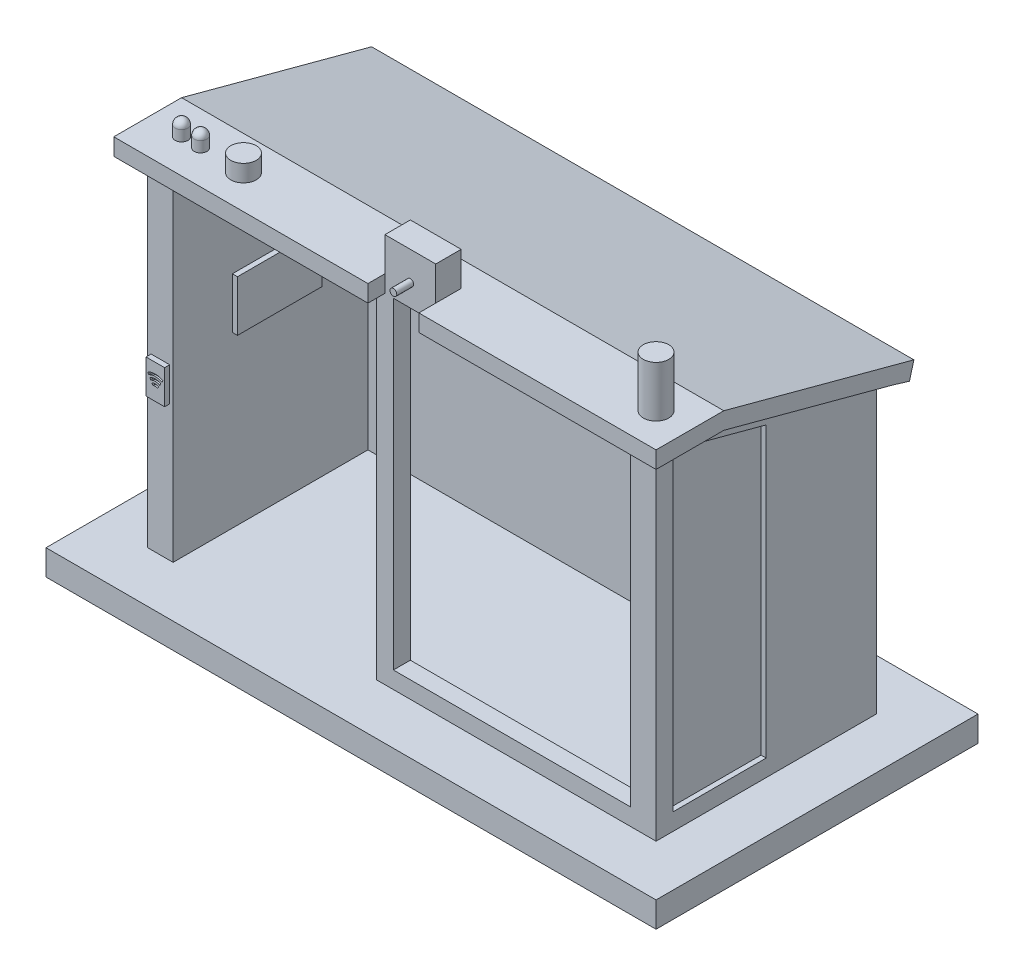
SolidWorks part; units mm, degrees
ref_plane "Alzado" through (0, 0, 0) normal (0, 0, 1) x (1, 0, 0)
ref_plane "Planta" through (0, 0, 0) normal (0, 1, 0) x (1, 0, 0)
ref_plane "Vista lateral" through (0, 0, 0) normal (1, 0, 0) x (0, 0, -1)
sketch "Croquis4" plane through (0, 0, 0) normal (0, 1, 0) x (1, 0, 0)
  line L0 (-150, 65) -> (150, -65) construction
  line L13 (-150, 65) -> (150, 65)
  line L14 (-150, 65) -> (-150, -65)
  line L15 (-150, -65) -> (-135, -65)
  line L16 (150, 65) -> (150, -65)
  line L17 (135, -65) -> (150, -65)
  line L19 (-135, -65) -> (-135, 50)
  line L20 (-135, 50) -> (135, 50)
  line L21 (135, -65) -> (135, 50)
  point P4 (0, 0)
  dimension "D1" = 15
  dimension "D2" = 130
  dimension "D3" = 300
  dimension "D4" = 15
  dimension "D5" = 15
extrude "Saliente-Extruir11" add sketch "Croquis4" along normal blind 200
sketch "Croquis28" plane through (-150, 0, 0) normal (-1, 0, 0) x (0, 0, 1)
  line L0 (-65, 173.2051) -> (35, 200)
  line L1 (-65, 200) -> (-65, 0) construction
  line L2 (-65, 200) -> (65, 200) construction
  line L3 (35, 200) -> (-65, 200)
  line L4 (-65, 200) -> (-65, 173.2051)
  line L5 (65, 200) -> (65, 0) construction
  dimension "D1" = 30
  dimension "D2" = 15
extrude "Cortar-Extruir10" cut sketch "Croquis28" against normal blind 300
sketch "Croquis29" plane through (-150, 0, 0) normal (-1, 0, 0) x (0, 0, 1)
  line L0 (-65, 173.2051) -> (35, 200)
  line L1 (35, 200) -> (65, 200)
  line L2 (65, 200) -> (75, 200)
  line L3 (75, 200) -> (75, 210)
  line L4 (75, 210) -> (35, 210)
  line L5 (35, 210) -> (-67.5, 182.5352)
  line L6 (-67.5, 182.5352) -> (-77.1593, 179.947)
  line L7 (-77.1593, 179.947) -> (-74.5711, 170.2878)
  line L8 (-74.5711, 170.2878) -> (-65, 173.2051)
extrude "Saliente-Extruir12" add sketch "Croquis29" against normal blind 310 and the other way blind 10
sketch "Croquis30" plane through (0, 0, 0) normal (0, -1, 0) x (1, 0, 0)
  line L0 (-180, 95) -> (180, -95) construction
  line L1 (-180, 95) -> (180, 95)
  line L2 (-180, 95) -> (-180, -95)
  line L3 (-180, -95) -> (180, -95)
  line L4 (180, 95) -> (180, -95)
  line L5 (-160, 75) -> (160, 75) construction
  line L6 (160, -65) -> (160, 35) construction
  point P4 (0, 0)
  dimension "D1" = 20
  dimension "D2" = 20
extrude "Saliente-Extruir13" add sketch "Croquis30" along normal blind 15
sketch "Croquis31" plane through (150, 0, 0) normal (1, 0, 0) x (0, 0, -1)
  line L0 (-55, 190) -> (-55, 10)
  line L1 (-55, 10) -> (0, 10)
  line L2 (0, 10) -> (0, 180.269)
  line L3 (0, 180.269) -> (-36.3165, 190)
  line L4 (-36.3165, 190) -> (-55, 190)
  line L5 (65, 173.2051) -> (-35, 200) construction
  line L6 (-65, 200) -> (-35, 200) construction
  line L7 (65, 173.2051) -> (-35, 200) construction
  line L8 (95, 0) -> (-95, 0) construction
  line L9 (-65, 200) -> (-65, 0) construction
  dimension "D1" = 10
  dimension "D2" = 10
  dimension "D3" = 10
  dimension "D4" = 10
extrude "Cortar-Extruir11" cut sketch "Croquis31" against normal blind 15
sketch "Croquis32" plane through (0, 10, 0) normal (0, 1, 0) x (1, 0, 0)
  line L0 (135, 0) -> (150, 0) construction
  line L1 (142, 0) -> (147, 0)
  line L2 (142, 0) -> (142, -55)
  line L3 (142, -55) -> (147, -55)
  line L4 (147, 0) -> (147, -55)
  line L5 (135, -55) -> (150, -55) construction
  line L6 (150, -55) -> (150, 0) construction
  line L7 (135, -55) -> (135, 0) construction
  dimension "D1" = 3
  dimension "D2" = 7
extrude "Saliente-Extruir14" add sketch "Croquis32" along normal blind 180
sketch "Croquis35" plane through (0, 0, 65) normal (0, 0, 1) x (1, 0, 0)
  line L2 (-150, 0) -> (-135, 0) construction
  line L3 (-148, 100) -> (-137, 100)
  line L4 (-148, 100) -> (-148, 80)
  line L5 (-148, 80) -> (-137, 80)
  line L6 (-137, 100) -> (-137, 80)
  line L7 (-150, 200) -> (-150, 0) construction
  line L8 (-135, 177.2243) -> (-135, 0) construction
  dimension "D1" = 100
  dimension "D2" = 80
  dimension "D3" = 2
  dimension "D4" = 2
extrude "Saliente-Extruir15" add sketch "Croquis35" along normal blind 3
sketch "Croquis36" plane through (0, 0, 68) normal (0, 0, 1) x (1, 0, 0)
  line L1 (-143.875, 87.3816) -> (-144.5, 88.4641)
  line L2 (-141.125, 87.3816) -> (-140.5, 88.4641)
  line L4 (-139.875, 89.5466) -> (-139.25, 90.6292)
  line L6 (-145.125, 89.5466) -> (-145.75, 90.6292)
  line L7 (-146.375, 91.7117) -> (-147, 92.7942)
  line L9 (-138.625, 91.7117) -> (-138, 92.7942)
  arc A0 (-140.5, 88.4641) -> (-144.5, 88.4641) centre (-142.5, 85) ccw
  arc A1 (-141.125, 87.3816) -> (-143.875, 87.3816) centre (-142.5, 85) ccw
  arc A2 (-139.875, 89.5466) -> (-145.125, 89.5466) centre (-142.5, 85) ccw
  arc A3 (-139.25, 90.6292) -> (-145.75, 90.6292) centre (-142.5, 85) ccw
  arc A4 (-138.625, 91.7117) -> (-146.375, 91.7117) centre (-142.5, 85) ccw
  arc A5 (-138, 92.7942) -> (-147, 92.7942) centre (-142.5, 85) ccw
  dimension "D1" = 5.5
  dimension "D2" = 8
  dimension "D3" = 10.5
  dimension "D4" = 13
  dimension "D6" = 15.5
  dimension "D8" = 18
  dimension "D9" = 60
extrude "Cortar-Extruir12" cut sketch "Croquis36" against normal blind 1
sketch "Croquis40" plane through (0, 0, 0) normal (0, 1, 0) x (1, 0, 0)
  line L1 (135, -65) -> (-15, -65)
  line L2 (135, -65) -> (135, -55)
  line L3 (135, -55) -> (-15, -55)
  line L4 (-15, -65) -> (-15, -55)
  dimension "D1" = 150
extrude "Saliente-Extruir16" add sketch "Croquis40" along normal blind 10
sketch "Croquis41" plane through (0, 10, 0) normal (0, 1, 0) x (1, 0, 0)
  line L1 (-15, -55) -> (-5, -55)
  line L2 (-15, -55) -> (-15, -65)
  line L3 (-15, -65) -> (-5, -65)
  line L4 (-5, -55) -> (-5, -65)
extrude "Saliente-Extruir17" add sketch "Croquis41" along normal blind 190
sketch "Croquis42" plane through (-135, 0, 0) normal (1, 0, 0) x (0, 0, -1)
  line L0 (50, 177.2243) -> (50, 0) construction
  line L1 (-30, 130) -> (20, 130)
  line L2 (-30, 130) -> (-30, 100)
  line L3 (-30, 100) -> (20, 100)
  line L4 (20, 130) -> (20, 100)
  line L5 (-65, 200) -> (-35, 200) construction
  dimension "D1" = 30
  dimension "D2" = 50
  dimension "D3" = 30
  dimension "D4" = 70
extrude "Saliente-Extruir18" add sketch "Croquis42" along normal blind 3
sketch "Croquis43" plane through (0, 210, 0) normal (0, 1, 0) x (1, 0, 0)
  line L0 (-160, -75) -> (160, -75) construction
  line L1 (-10, -65) -> (20, -65)
  line L2 (-10, -65) -> (-10, -75)
  line L3 (-10, -75) -> (20, -75)
  line L4 (20, -65) -> (20, -75)
  line L5 (-160, -75) -> (-160, -35) construction
  dimension "D1" = 10
  dimension "D2" = 30
  dimension "D3" = 150
extrude "Cortar-Extruir13" cut sketch "Croquis43" against normal blind 10
sketch "Croquis44" plane through (0, 210, 0) normal (0, 1, 0) x (1, 0, 0)
  line L0 (20, -75) -> (160, -75) construction
  line L1 (160, -75) -> (160, -35) construction
  circle A0 centre (140, -55) radius 7.5
  dimension "D1" = 15
  dimension "D2" = 20
  dimension "D3" = 20
extrude "Saliente-Extruir19" add sketch "Croquis44" along normal blind 30
sketch "Croquis45" plane through (0, 210, 0) normal (0, 1, 0) x (1, 0, 0)
  line L1 (-10, -65) -> (20, -65)
  line L2 (-10, -65) -> (-10, -50)
  line L3 (-10, -50) -> (20, -50)
  line L4 (20, -65) -> (20, -50)
  dimension "D1" = 15
extrude "Saliente-Extruir20" add sketch "Croquis45" along normal blind 20
sketch "Croquis47" plane through (0, 0, 65) normal (0, 0, 1) x (1, 0, 0)
  line L0 (-10, 230) -> (20, 200) construction
  circle A0 centre (5, 215) radius 2
  point P7 (5, 215)
extrude "Saliente-Extruir21" add sketch "Croquis47" along normal blind 10
sketch "Croquis49" plane through (0, 0, 75) normal (0, 0, 1) x (1, 0, 0)
  circle A0 centre (5, 215) radius 2
  dimension "D1" = 4
extrude "Cortar-Extruir14" cut sketch "Croquis49" against normal blind 10
sketch "Croquis50" plane through (0, 0, 65) normal (0, 0, 1) x (1, 0, 0)
  line L0 (-10, 230) -> (20, 200) construction
  line L1 (-135, 200) -> (135, 200) construction
  line L2 (20, 200) -> (20, 210) construction
  circle A0 centre (5, 213) radius 2
  point P10 (5, 215)
  dimension "D1" = 2
extrude "Saliente-Extruir22" add sketch "Croquis50" along normal blind 10
sketch "Croquis52" plane through (0, 210, 0) normal (0, 1, 0) x (1, 0, 0)
  line L0 (-160, -75) -> (-160, -35) construction
  line L1 (-160, -75) -> (-10, -75) construction
  circle A0 centre (-140, -55) radius 3.75
  circle A1 centre (-128.7599, -55) radius 3.75
  point P4 (0, 0)
  dimension "D1" = 20
  dimension "D2" = 20
extrude "Saliente-Extruir29" add sketch "Croquis52" along normal blind 10
fillet "Redondeo6" radius 3.7 2 edges at (-140, 220, 58.75) (-128.7599, 220, 58.75)
sketch "Croquis53" plane through (0, 210, 0) normal (0, 1, 0) x (1, 0, 0)
  line L0 (-160, -75) -> (-160, -35) construction
  circle A0 centre (-103.45, -55) radius 7.5
  point P6 (-160, -55)
  dimension "D1" = 15
extrude "Saliente-Extruir30" add sketch "Croquis53" along normal blind 10 contours A0
